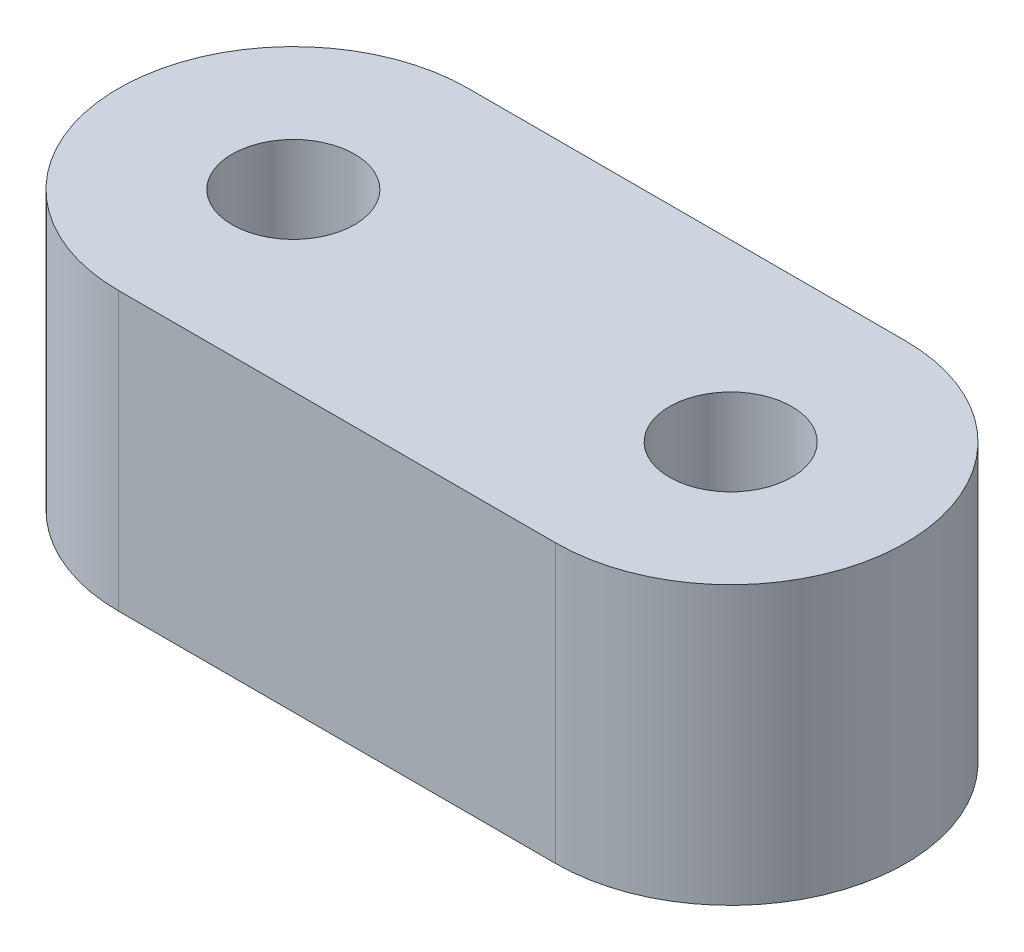
SolidWorks part; units mm, degrees
ref_plane "Front Plane" through (0, 0, 0) normal (0, 0, 1) x (1, 0, 0)
ref_plane "Top Plane" through (0, 0, 0) normal (0, 1, 0) x (1, 0, 0)
ref_plane "Right Plane" through (0, 0, 0) normal (1, 0, 0) x (0, 0, -1)
sketch "Sketch1" plane through (0, 0, 0) normal (0, 1, 0) x (1, 0, 0)
  line L0 (5, 0) -> (-5, 0) construction
  line L1 (5, -4) -> (-5, -4)
  line L2 (5, 4) -> (-5, 4)
  arc A0 (5, -4) -> (5, 4) centre (5, 0) ccw
  arc A1 (-5, 4) -> (-5, -4) centre (-5, 0) ccw
  circle A2 centre (-5, 0) radius 1.4
  circle A3 centre (5, 0) radius 1.4
  point P2 (0, 0)
  dimension "D1" = 2.8
  dimension "D3" = 4
  dimension "D2" = 5
extrude "Boss-Extrude1" add sketch "Sketch1" along normal blind 6.35
